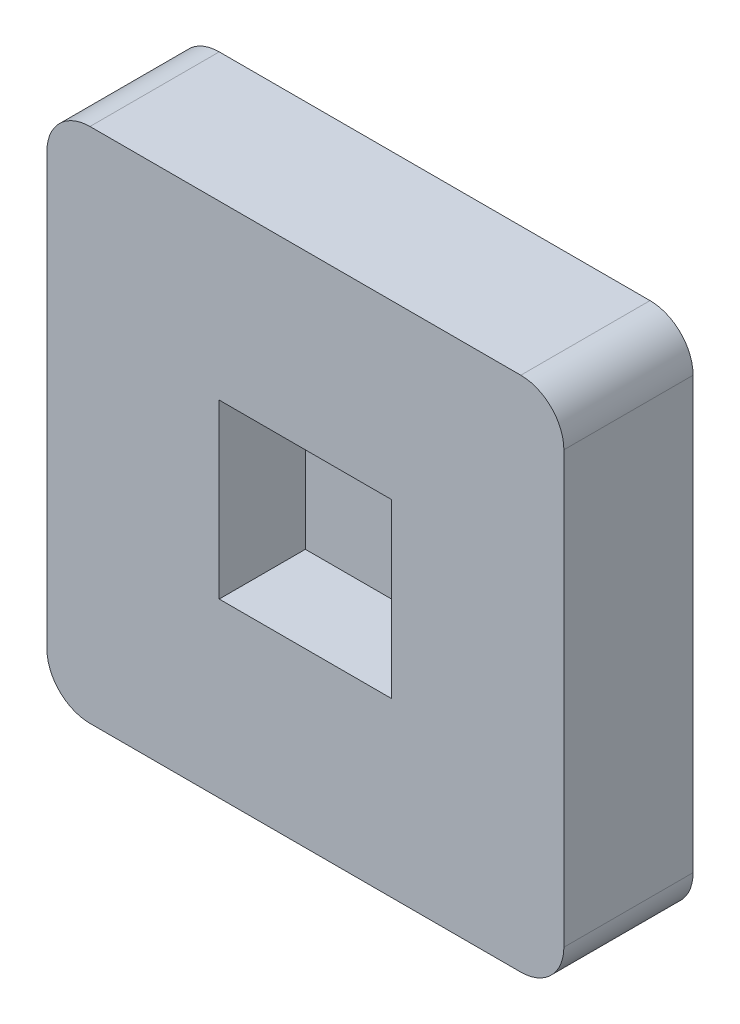
SolidWorks part; units mm, degrees
ref_plane "정면" through (0, 0, 0) normal (0, 0, 1) x (1, 0, 0)
ref_plane "윗면" through (0, 0, 0) normal (0, 1, 0) x (1, 0, 0)
ref_plane "우측면" through (0, 0, 0) normal (1, 0, 0) x (0, 0, -1)
sketch "스케치1" plane through (0, 0, 0) normal (0, 0, 1) x (1, 0, 0)
  line L1 (-6, -6) -> (6, -6)
  line L2 (-6, -6) -> (-6, 6)
  line L3 (-6, 6) -> (6, 6)
  line L4 (6, -6) -> (6, 6)
  line L5 (-6, -6) -> (6, 6) construction
  line L6 (-6, 6) -> (6, -6) construction
  point P0 (0, 0)
  dimension "D1" = 12
  dimension "D2" = 12
extrude "보스-돌출1" add sketch "스케치1" along normal blind 3
sketch "스케치2" plane through (0, 0, 3) normal (0, 0, 1) x (1, 0, 0)
  line L1 (-2, -2) -> (2, -2)
  line L2 (-2, -2) -> (-2, 2)
  line L3 (-2, 2) -> (2, 2)
  line L4 (2, -2) -> (2, 2)
  line L5 (-2, -2) -> (2, 2) construction
  line L6 (-2, 2) -> (2, -2) construction
  point P0 (0, 0)
  dimension "D1" = 4
  dimension "D2" = 4
extrude "컷-돌출1" cut sketch "스케치2" against normal blind 2
fillet "필렛1" radius 1 4 edges at (6, -6, 1.5) (-6, -6, 1.5) (-6, 6, 1.5) (6, 6, 1.5)
